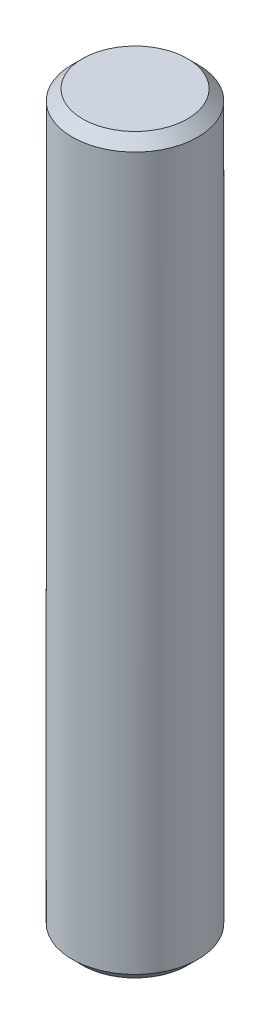
SolidWorks part; units mm, degrees
ref_plane "Front Plane" through (0, 0, 0) normal (0, 0, 1) x (1, 0, 0)
ref_plane "Top Plane" through (0, 0, 0) normal (0, 1, 0) x (1, 0, 0)
ref_plane "Right Plane" through (0, 0, 0) normal (1, 0, 0) x (0, 0, -1)
sketch "Sketch2" plane through (0, 0, 0) normal (0, 0, 1) x (1, 0, 0)
  line L1 (0, 0) -> (6, 0)
  line L2 (0, 0) -> (0, 70)
  line L3 (0, 70) -> (6, 70)
  line L4 (6, 0) -> (6, 70)
  dimension "D1" = 6
  dimension "D2" = 70
revolve "Revolve1" add sketch "Sketch2" angle 360 about L2
cosmetic thread "Cosmetic Thread1" parameters "D1"=40, "D2"=10.072
cosmetic thread "Cosmetic Thread2" parameters "D1"=14, "D2"=10.072
chamfer "Chamfer1" distance 1 angle 45 2 edges at (0, 0, -6) (0, 70, -6)
